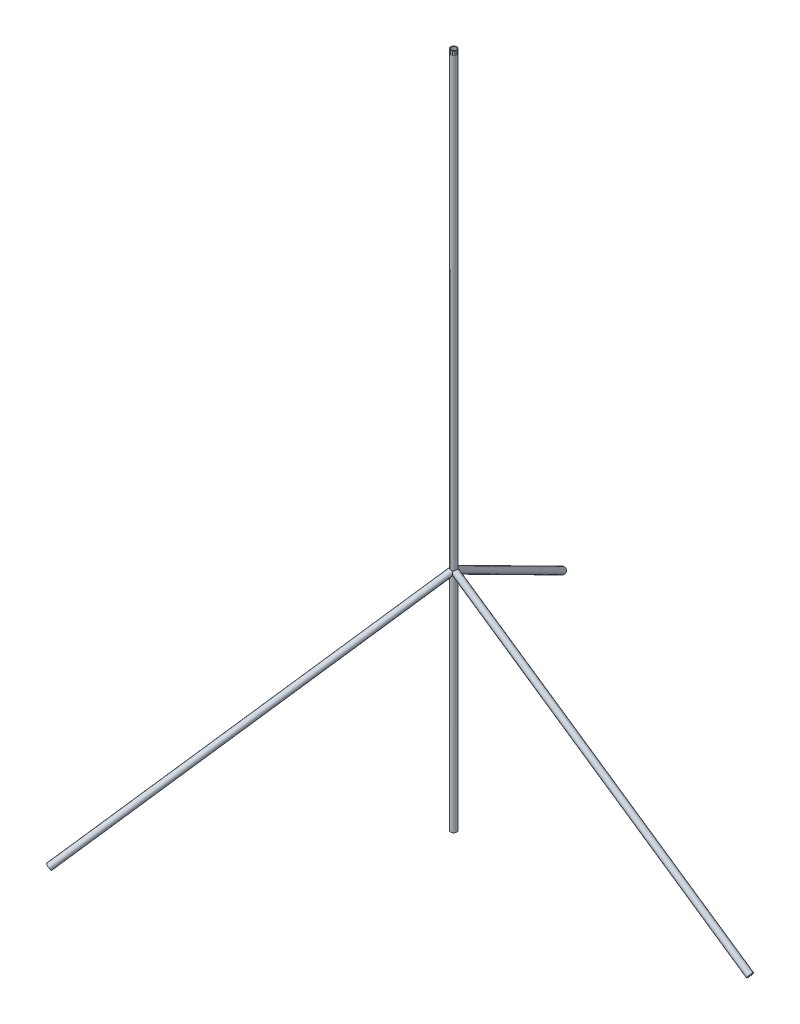
SolidWorks part; units mm, degrees
material "6061-T6 (SS)"
ref_plane "Front Plane" through (0, 0, 0) normal (0, 0, 1) x (1, 0, 0)
ref_plane "Top Plane" through (0, 0, 0) normal (0, 1, 0) x (1, 0, 0)
ref_plane "Right Plane" through (0, 0, 0) normal (1, 0, 0) x (0, 0, -1)
sketch "Sketch1" plane through (0, 0, 0) normal (0, 1, 0) x (1, 0, 0)
  circle A0 centre (0, 0) radius 16.2306
  circle A1 centre (0, 0) radius 21.082
  dimension "D1" = 32.4612
  dimension "D2" = 4.8514
extrude "Boss-Extrude1" add sketch "Sketch1" along normal blind 4572
sketch3d "3DSketch1"
  line L0 (0, 0, 0) -> (0, 1524, 0) construction
  line L1 (0, 1524, 0) -> (2001.1155, 152.4, 0)
  line L2 (0, 0, 0) -> (2001.1155, 0, 0) construction
  line L3 (2001.1155, 0, 0) -> (2001.1155, 152.4, 0) construction
  point P6 (0, 0, 0)
  dimension "D1" = 152.4
  dimension "D2" = 1524
ref_plane "Plane1" through (2001.1155, 152.4, 0) normal (0.8248, -0.5654, 0) x (0, 0, -1)
sketch "Sketch2" plane through (2001.1155, 152.4, 0) normal (0.8248, -0.5654, 0) x (0, 0, -1)
  circle A0 centre (0, 0) radius 16.2306
  circle A1 centre (0, 0) radius 21.082
  dimension "D1" = 32.4612
  dimension "D2" = 4.8514
sweep "Sweep1" add profiles "Sketch2" path "3DSketch1"
pattern_circular "CirPattern1" count 3 over 360 about axis through (0, 0, 0) along (0, 1, 0) of "Sweep1"
sketch "Sketch3" plane through (0, 4572, 0) normal (0, 1, 0) x (1, 0, 0)
  line L1 (21.8257, 0) -> (18.9016, 10.9128)
  line L2 (18.9016, 10.9128) -> (10.9128, 18.9016)
  line L3 (10.9128, 18.9016) -> (0, 21.8257)
  line L4 (0, 21.8257) -> (-10.9128, 18.9016)
  line L5 (-10.9128, 18.9016) -> (-18.9016, 10.9128)
  line L6 (-18.9016, 10.9128) -> (-21.8257, 0)
  line L7 (-21.8257, 0) -> (-18.9016, -10.9128)
  line L8 (-18.9016, -10.9128) -> (-10.9128, -18.9016)
  line L9 (-10.9128, -18.9016) -> (0, -21.8257)
  line L10 (0, -21.8257) -> (10.9128, -18.9016)
  line L11 (10.9128, -18.9016) -> (18.9016, -10.9128)
  line L12 (18.9016, -10.9128) -> (21.8257, 0)
  circle A0 centre (0, 0) radius 21.082 construction
  circle A1 centre (0, 0) radius 21.082 construction
  circle A2 centre (0, 0) radius 16.2306
  circle A3 centre (0, 0) radius 16.2306 construction
extrude "Boss-Extrude2" add sketch "Sketch3" against normal blind 25.4
sketch "Sketch4" plane through (0, 4572, 0) normal (0, 1, 0) x (1, 0, 0)
  circle A0 centre (0, 0) radius 16.2306
  circle A1 centre (0, 0) radius 16.2306 construction
extrude "Cut-Extrude1" cut sketch "Sketch4" against normal through all
